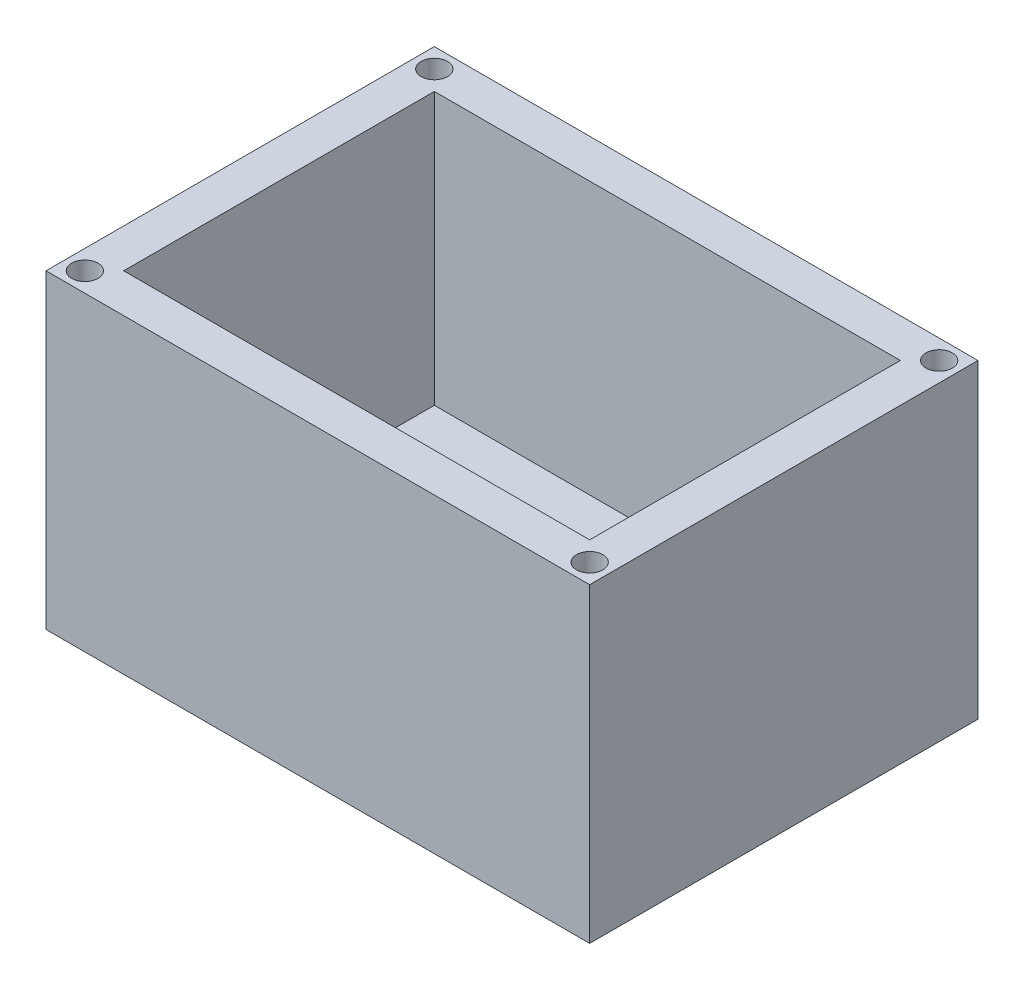
SolidWorks part; units mm, degrees
ref_plane "Alzado" through (0, 0, 0) normal (0, 0, 1) x (1, 0, 0)
ref_plane "Planta" through (0, 0, 0) normal (0, 1, 0) x (1, 0, 0)
ref_plane "Vista lateral" through (0, 0, 0) normal (1, 0, 0) x (0, 0, -1)
sketch "Croquis1" plane through (0, 0, 0) normal (0, 1, 0) x (1, 0, 0)
  line L0 (-24.9817, 14.2814) -> (45.0183, 14.2814)
  line L1 (45.0183, 14.2814) -> (45.0183, -35.7186)
  line L2 (45.0183, -35.7186) -> (-24.9817, -35.7186)
  line L3 (-24.9817, 14.2814) -> (-24.9817, -35.7186)
  dimension "D1" = 70
  dimension "D2" = 50
extrude "Saliente-Extruir1" add sketch "Croquis1" along normal blind 40
sketch "Croquis2" plane through (0, 0, 0) normal (0, 1, 0) x (1, 0, 0)
  line L0 (45.0183, -35.7186) -> (45.0183, 14.2814) construction
  line L1 (-19.9817, 9.2814) -> (40.0183, 9.2814)
  line L2 (-19.9817, 9.2814) -> (-19.9817, -30.7186)
  line L3 (-19.9817, -30.7186) -> (40.0183, -30.7186)
  line L4 (40.0183, 9.2814) -> (40.0183, -30.7186)
  line L5 (-24.9817, -35.7186) -> (45.0183, -35.7186) construction
  dimension "D1" = 40
  dimension "D2" = 60
  dimension "D3" = 5
  dimension "D4" = 5
extrude "Cortar-Extruir1" cut sketch "Croquis2" along normal through all
sketch "Croquis3" plane through (0, 0, 0) normal (0, 1, 0) x (1, 0, 0)
  line L1 (-19.9817, 9.2814) -> (40.0183, 9.2814)
  line L2 (-19.9817, 9.2814) -> (-19.9817, -30.7186)
  line L3 (-19.9817, -30.7186) -> (40.0183, -30.7186)
  line L4 (40.0183, 9.2814) -> (40.0183, -30.7186)
extrude "Saliente-Extruir2" add sketch "Croquis3" along normal blind 5
ref_plane "Plano1" through (0, 40, 0) normal (0, -1, 0) x (-1, 0, 0)
sketch "Croquis5" plane through (0, 40, 0) normal (0, -1, 0) x (-1, 0, 0)
  line L0 (-45.0183, 14.2814) -> (24.9817, 14.2814) construction
  line L1 (24.9817, 14.2814) -> (24.9817, -35.7186) construction
  line L2 (-45.0183, -35.7186) -> (-45.0183, 14.2814) construction
  line L3 (24.9817, -35.7186) -> (-45.0183, -35.7186) construction
  point P0 (22.4817, 11.7814)
  point P1 (-42.5183, 11.7814)
  point P2 (-42.5183, -33.2186)
  point P3 (22.4817, -33.2186)
  dimension "D1" = 2.5
  dimension "D2" = 2.5
  dimension "D3" = 2.5
  dimension "D4" = 2.5
  dimension "D5" = 2.5
  dimension "D6" = 2.5
  dimension "D7" = 2.5
  dimension "D8" = 2.5
hole_wizard "Taladro de margen para M31" positions "Croquis3D2" profile "Croquis7" hole size "M3" standard "DIN"
sketch3d "Croquis3D2"
  point P0 (-22.4817, 40, -11.7814)
  point P2 (42.5183, 40, -11.7814)
  point P4 (42.5183, 40, 33.2186)
  point P7 (42.5183, 40, 33.2186)
  point P9 (-22.4817, 40, 33.2186)
sketch "Croquis7" plane through (-22.4817, 40, -11.7814) normal (1, 0, 0) x (0, 0, 1)
  line L0 (0, 0) -> (0, 21.0215)
  line L1 (0, 21.0215) -> (1.7, 20)
  line L2 (1.7, 20) -> (1.7, 0)
  line L5 (1.7, 0) -> (0, 0)
  line L10 (0, 21.0215) -> (-1.7, 20) construction
  line L11 (0, -6.35) -> (0, 107.95) construction
  dimension "Diámetro de taladro" = 3.4
  dimension "Profundidad de taladro" = 20
  dimension "Ángulo de perforador" = 118
